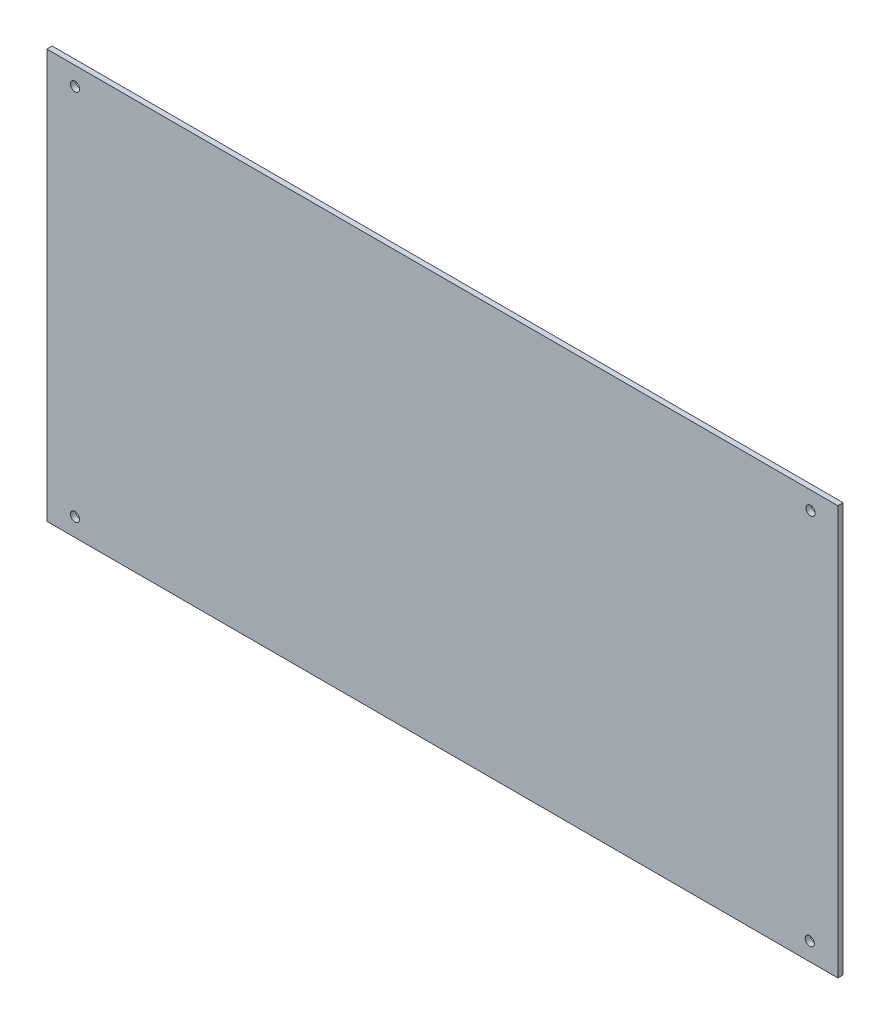
SolidWorks part; units mm, degrees
ref_plane "Plan de face" through (0, 0, 0) normal (0, 0, 1) x (1, 0, 0)
ref_plane "Plan de dessus" through (0, 0, 0) normal (0, 1, 0) x (1, 0, 0)
ref_plane "Plan de droite" through (0, 0, 0) normal (1, 0, 0) x (0, 0, -1)
sketch "Esquisse1" plane through (0, 0, 0) normal (0, 0, 1) x (1, 0, 0)
  line L1 (0, 0) -> (-450.3, 0)
  line L2 (0, 0) -> (0, 232.85)
  line L3 (0, 232.85) -> (-450.3, 232.85)
  line L4 (-450.3, 0) -> (-450.3, 232.85)
  dimension "D1" = 232.85
  dimension "D2" = 450.3
extrude "Boss.-Extru.1" add sketch "Esquisse1" along normal blind 3
sketch "Esquisse2" plane through (0, 0, 3) normal (0, 0, 1) x (1, 0, 0)
  circle A0 centre (-434.3, 10.2368) radius 2.6 construction
  circle A1 centre (-16, 10.2368) radius 2.6 construction
  circle A2 centre (-15.549, 222.6722) radius 2.6 construction
  circle A3 centre (-434.3, 222.3873) radius 2.6 construction
  circle A4 centre (-434.3, 10.2368) radius 2.6
  circle A5 centre (-16, 10.2368) radius 2.6
  circle A6 centre (-15.549, 222.6722) radius 2.6
  circle A7 centre (-434.3, 222.3873) radius 2.6
extrude "Enlèv. mat.-Extru.1" cut sketch "Esquisse2" against normal blind 20
